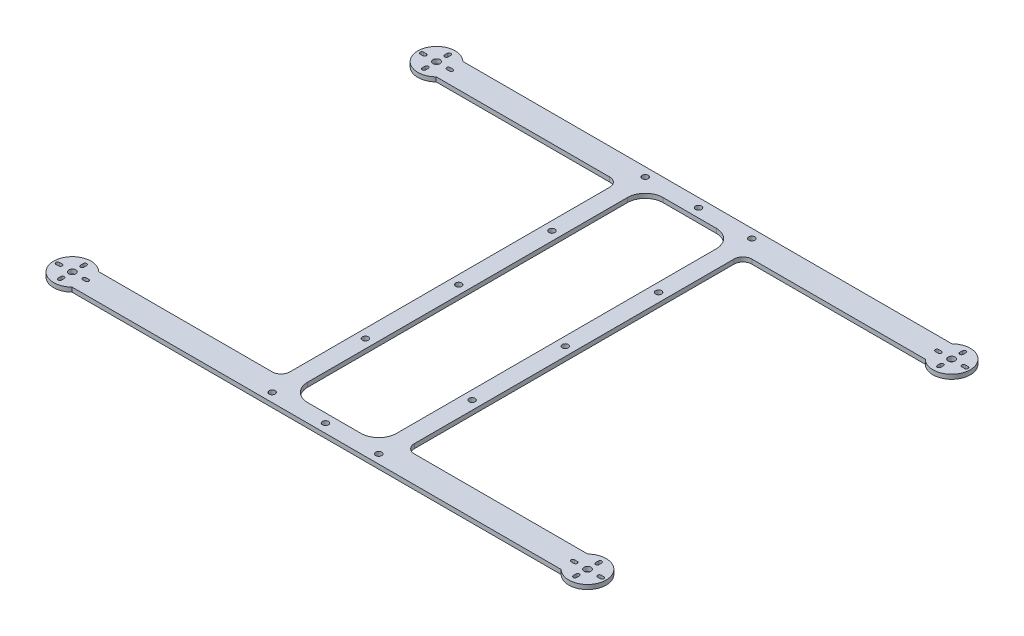
SolidWorks part; units mm, degrees
ref_plane "Front Plane" through (0, 0, 0) normal (0, 0, 1) x (1, 0, 0)
ref_plane "Top Plane" through (0, 0, 0) normal (0, 1, 0) x (1, 0, 0)
ref_plane "Right Plane" through (0, 0, 0) normal (1, 0, 0) x (0, 0, -1)
sketch "Sketch1" plane through (0, 0, 0) normal (0, 1, 0) x (1, 0, 0)
  line L1 (-44.45, 139.7) -> (44.45, 139.7)
  line L2 (-44.45, 120.65) -> (-44.45, -120.65)
  line L3 (-44.45, -139.7) -> (44.45, -139.7)
  line L4 (44.45, 120.65) -> (44.45, -120.65)
  line L5 (44.45, 139.7) -> (184.15, 139.7)
  line L7 (44.45, 120.65) -> (184.15, 120.65)
  line L8 (184.15, 139.7) -> (184.15, 120.65)
  line L14 (0, 0) -> (0, 187.5455) construction
  line L17 (0, 0) -> (-239.6804, 0) construction
  line L21 (0, 0) -> (44.45, 0) construction
  line L22 (-44.45, 120.65) -> (-184.15, 120.65)
  line L23 (-44.45, 139.7) -> (-184.15, 139.7)
  line L24 (-184.15, 139.7) -> (-184.15, 120.65)
  line L37 (-31.75, 127) -> (31.75, 127)
  line L40 (-31.75, 127) -> (-31.75, -127)
  line L43 (-31.75, -127) -> (31.75, -127)
  line L46 (31.75, 127) -> (31.75, -127)
  line L49 (44.45, -120.65) -> (184.15, -120.65)
  line L50 (44.45, -139.7) -> (184.15, -139.7)
  line L51 (184.15, -139.7) -> (184.15, -120.65)
  line L88 (-184.15, -139.7) -> (-184.15, -120.65)
  line L89 (-44.45, -139.7) -> (-184.15, -139.7)
  line L90 (-44.45, -120.65) -> (-184.15, -120.65)
  point P4 (0, 139.7)
  point P6 (-44.45, 0)
  dimension "D4" = 139.7
  dimension "D1" = 279.4
  dimension "D2" = 88.9
  dimension "D3" = 19.05
  dimension "D6" = 12.7
  dimension "D7" = 12.7
  dimension "D8" = 12.7
  dimension "D10" = 139.7
  dimension "D12" = 12.7
  dimension "D18" = 19.05
extrude "Boss-Extrude1" add sketch "Sketch1" along normal blind 3.175
sketch "Sketch4" plane through (0, 3.175, 0) normal (0, 1, 0) x (1, 0, 0)
  line L0 (184.15, 120.65) -> (184.15, 139.7) construction
  line L1 (-184.15, 139.7) -> (-184.15, 120.65) construction
  line L2 (-184.15, -120.65) -> (-184.15, -139.7) construction
  line L3 (184.15, -139.7) -> (184.15, -120.65) construction
  circle A0 centre (184.15, 130.175) radius 13.335
  circle A1 centre (-184.15, 130.175) radius 13.335
  circle A2 centre (-184.15, -130.175) radius 13.335
  circle A3 centre (184.15, -130.175) radius 13.335
  point P18 (184.15, -130.175)
extrude "Boss-Extrude4" add sketch "Sketch4" against normal up to surface (3.175 mm away) up to face at (0, 0, 0)
sketch "Sketch5" plane through (0, 3.175, 0) normal (0, 1, 0) x (1, 0, 0)
  line L0 (173.65, 130.175) -> (175.65, 130.175) construction
  line L1 (173.65, 131.425) -> (175.65, 131.425)
  line L2 (173.65, 128.925) -> (175.65, 128.925)
  line L3 (184.15, 130.175) -> (184.15, 143.51) construction
  line L4 (194.65, 130.175) -> (192.65, 130.175) construction
  line L5 (194.65, 131.425) -> (192.65, 131.425)
  line L6 (194.65, 128.925) -> (192.65, 128.925)
  line L7 (184.15, 139.175) -> (184.15, 137.175) construction
  line L8 (185.4, 139.175) -> (185.4, 137.175)
  line L9 (182.9, 139.175) -> (182.9, 137.175)
  line L10 (184.15, 130.175) -> (197.485, 130.175) construction
  line L11 (184.15, 121.175) -> (184.15, 123.175) construction
  line L12 (185.4, 121.175) -> (185.4, 123.175)
  line L13 (182.9, 121.175) -> (182.9, 123.175)
  line L14 (0, 0) -> (0, 263.0018) construction
  line L15 (0, 0) -> (558.7896, 0) construction
  line L16 (-173.65, 130.175) -> (-175.65, 130.175) construction
  line L17 (-173.65, 131.425) -> (-175.65, 131.425)
  line L18 (-173.65, 128.925) -> (-175.65, 128.925)
  line L19 (-194.65, 130.175) -> (-192.65, 130.175) construction
  line L20 (-194.65, 131.425) -> (-192.65, 131.425)
  line L21 (-194.65, 128.925) -> (-192.65, 128.925)
  line L22 (-184.15, 139.175) -> (-184.15, 137.175) construction
  line L23 (-185.4, 139.175) -> (-185.4, 137.175)
  line L24 (-182.9, 139.175) -> (-182.9, 137.175)
  line L25 (-184.15, 121.175) -> (-184.15, 123.175) construction
  line L26 (-185.4, 121.175) -> (-185.4, 123.175)
  line L27 (-182.9, 121.175) -> (-182.9, 123.175)
  line L28 (-184.15, 130.175) -> (-197.485, 130.175) construction
  line L29 (-184.15, 130.175) -> (-184.15, 143.51) construction
  line L30 (173.65, -130.175) -> (175.65, -130.175) construction
  line L31 (173.65, -131.425) -> (175.65, -131.425)
  line L32 (173.65, -128.925) -> (175.65, -128.925)
  line L33 (184.15, -139.175) -> (184.15, -137.175) construction
  line L34 (185.4, -139.175) -> (185.4, -137.175)
  line L35 (182.9, -139.175) -> (182.9, -137.175)
  line L36 (194.65, -130.175) -> (192.65, -130.175) construction
  line L37 (194.65, -131.425) -> (192.65, -131.425)
  line L38 (194.65, -128.925) -> (192.65, -128.925)
  line L39 (184.15, -121.175) -> (184.15, -123.175) construction
  line L40 (185.4, -121.175) -> (185.4, -123.175)
  line L41 (182.9, -121.175) -> (182.9, -123.175)
  line L42 (184.15, -130.175) -> (197.485, -130.175) construction
  line L43 (184.15, -130.175) -> (184.15, -143.51) construction
  line L44 (-184.15, -130.175) -> (-184.15, -143.51) construction
  line L45 (-184.15, -130.175) -> (-197.485, -130.175) construction
  line L46 (-184.15, -121.175) -> (-184.15, -123.175) construction
  line L47 (-185.4, -121.175) -> (-185.4, -123.175)
  line L48 (-182.9, -121.175) -> (-182.9, -123.175)
  line L49 (-184.15, -139.175) -> (-184.15, -137.175) construction
  line L50 (-185.4, -139.175) -> (-185.4, -137.175)
  line L51 (-182.9, -139.175) -> (-182.9, -137.175)
  line L52 (-194.65, -130.175) -> (-192.65, -130.175) construction
  line L53 (-194.65, -131.425) -> (-192.65, -131.425)
  line L54 (-194.65, -128.925) -> (-192.65, -128.925)
  line L55 (-173.65, -130.175) -> (-175.65, -130.175) construction
  line L56 (-173.65, -131.425) -> (-175.65, -131.425)
  line L57 (-173.65, -128.925) -> (-175.65, -128.925)
  circle A0 centre (184.15, 130.175) radius 2.5
  arc A1 (173.65, 131.425) -> (173.65, 128.925) centre (173.65, 130.175) ccw
  arc A2 (175.65, 128.925) -> (175.65, 131.425) centre (175.65, 130.175) ccw
  arc A3 (174.8174, 120.65) -> (174.8174, 139.7) centre (184.15, 130.175) ccw construction
  arc A4 (194.65, 131.425) -> (194.65, 128.925) centre (194.65, 130.175) cw
  arc A5 (192.65, 128.925) -> (192.65, 131.425) centre (192.65, 130.175) cw
  arc A6 (185.4, 139.175) -> (182.9, 139.175) centre (184.15, 139.175) ccw
  arc A7 (182.9, 137.175) -> (185.4, 137.175) centre (184.15, 137.175) ccw
  arc A8 (185.4, 121.175) -> (182.9, 121.175) centre (184.15, 121.175) cw
  arc A9 (182.9, 123.175) -> (185.4, 123.175) centre (184.15, 123.175) cw
  arc A10 (-173.65, 131.425) -> (-173.65, 128.925) centre (-173.65, 130.175) cw
  arc A11 (-175.65, 128.925) -> (-175.65, 131.425) centre (-175.65, 130.175) cw
  arc A12 (-194.65, 131.425) -> (-194.65, 128.925) centre (-194.65, 130.175) ccw
  arc A13 (-192.65, 128.925) -> (-192.65, 131.425) centre (-192.65, 130.175) ccw
  arc A14 (-185.4, 139.175) -> (-182.9, 139.175) centre (-184.15, 139.175) cw
  arc A15 (-182.9, 137.175) -> (-185.4, 137.175) centre (-184.15, 137.175) cw
  arc A16 (-185.4, 121.175) -> (-182.9, 121.175) centre (-184.15, 121.175) ccw
  arc A17 (-182.9, 123.175) -> (-185.4, 123.175) centre (-184.15, 123.175) ccw
  circle A18 centre (-184.15, 130.175) radius 2.5
  arc A19 (173.65, -131.425) -> (173.65, -128.925) centre (173.65, -130.175) cw
  arc A20 (175.65, -128.925) -> (175.65, -131.425) centre (175.65, -130.175) cw
  arc A21 (185.4, -139.175) -> (182.9, -139.175) centre (184.15, -139.175) cw
  arc A22 (182.9, -137.175) -> (185.4, -137.175) centre (184.15, -137.175) cw
  arc A23 (194.65, -131.425) -> (194.65, -128.925) centre (194.65, -130.175) ccw
  arc A24 (192.65, -128.925) -> (192.65, -131.425) centre (192.65, -130.175) ccw
  arc A25 (185.4, -121.175) -> (182.9, -121.175) centre (184.15, -121.175) ccw
  arc A26 (182.9, -123.175) -> (185.4, -123.175) centre (184.15, -123.175) ccw
  circle A27 centre (184.15, -130.175) radius 2.5
  circle A28 centre (-184.15, -130.175) radius 2.5
  arc A29 (-185.4, -121.175) -> (-182.9, -121.175) centre (-184.15, -121.175) cw
  arc A30 (-182.9, -123.175) -> (-185.4, -123.175) centre (-184.15, -123.175) cw
  arc A31 (-185.4, -139.175) -> (-182.9, -139.175) centre (-184.15, -139.175) ccw
  arc A32 (-182.9, -137.175) -> (-185.4, -137.175) centre (-184.15, -137.175) ccw
  arc A33 (-194.65, -131.425) -> (-194.65, -128.925) centre (-194.65, -130.175) cw
  arc A34 (-192.65, -128.925) -> (-192.65, -131.425) centre (-192.65, -130.175) cw
  arc A35 (-173.65, -131.425) -> (-173.65, -128.925) centre (-173.65, -130.175) ccw
  arc A36 (-175.65, -128.925) -> (-175.65, -131.425) centre (-175.65, -130.175) ccw
  point P5 (174.65, 130.175)
  point P16 (193.65, 130.175)
  point P23 (184.15, 138.175)
  point P31 (184.15, 122.175)
  point P42 (-174.65, 130.175)
  point P49 (-193.65, 130.175)
  point P56 (-184.15, 138.175)
  point P63 (-184.15, 122.175)
  point P74 (174.65, -130.175)
  point P81 (184.15, -138.175)
  point P88 (193.65, -130.175)
  point P95 (184.15, -122.175)
  point P110 (-184.15, -122.175)
  point P117 (-184.15, -138.175)
  point P124 (-193.65, -130.175)
  point P131 (-174.65, -130.175)
  dimension "D1" = 5
  dimension "D2" = 2.5
  dimension "D3" = 2
  dimension "D4" = 19
  dimension "D5" = 2.5
  dimension "D6" = 2
  dimension "D7" = 16
extrude "Motor Holes" cut sketch "Sketch5" against normal through all
sketch "Sketch7" plane through (0, 3.175, 0) normal (0, 1, 0) x (1, 0, 0)
  line L0 (174.8174, 139.7) -> (-174.8174, 139.7) construction
  line L1 (-44.45, 120.65) -> (-44.45, -120.65) construction
  line L2 (0, 0) -> (0, 246.0772) construction
  line L3 (0, 0) -> (301.4392, 0) construction
  circle A0 centre (-38.1, 133.35) radius 2.159
  circle A1 centre (-38.1, 66.675) radius 2.159
  circle A2 centre (-38.1, 0) radius 2.159
  circle A3 centre (-38.1, -66.675) radius 2.159
  circle A5 centre (-38.1, -133.35) radius 2.159
  circle A6 centre (38.1, -133.35) radius 2.159
  circle A7 centre (38.1, -66.675) radius 2.159
  circle A8 centre (38.1, 0) radius 2.159
  circle A9 centre (38.1, 66.675) radius 2.159
  circle A10 centre (38.1, 133.35) radius 2.159
  circle A11 centre (0, 133.35) radius 2.159
  circle A12 centre (0, -133.35) radius 2.159
  dimension "D1" = 4.318
  dimension "D2" = 6.35
  dimension "D3" = 6.35
  dimension "D4" = 66.675
  dimension "D5" = 66.675
  dimension "D6" = 66.675
  dimension "D7" = 66.675
extrude "Cut-Extrude2" cut sketch "Sketch7" against normal through all
fillet "Fillet1" radius 12.7 4 edges at (31.75, 1.5875, 127) (-31.75, 1.5875, 127) (-31.75, 1.5875, -127) (31.75, 1.5875, -127)
fillet "Fillet2" radius 6.35 4 edges at (-44.45, 1.5875, 120.65) (-44.45, 1.5875, -120.65) (44.45, 1.5875, -120.65) (44.45, 1.5875, 120.65)
sketch "Sketch8" plane through (0, 3.175, 0) normal (0, 1, 0) x (1, 0, 0)
  line L0 (174.8174, 139.7) -> (-174.8174, 139.7) construction
  line L1 (0, 139.7) -> (0, 110.7046) construction
  circle A0 centre (-15.7442, 133.35) radius 2.159
  circle A1 centre (15.7442, 133.35) radius 2.159
  dimension "D5" = 4.318
  dimension "D6" = 4.318
  dimension "D1" = 6.35
  dimension "D2" = 6.35
  dimension "D3" = 31.4884
  dimension "D4" = 15.7442
